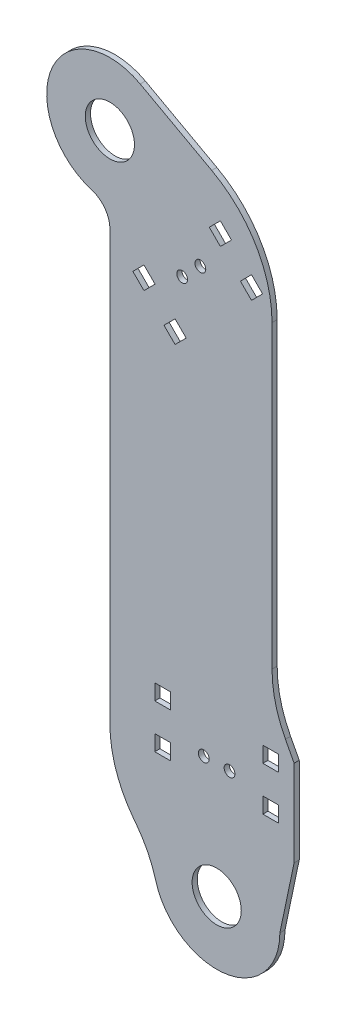
SolidWorks part; units mm, degrees
ref_plane "前视基准面" through (0, 0, 0) normal (0, 0, 1) x (1, 0, 0)
ref_plane "上视基准面" through (0, 0, 0) normal (0, 1, 0) x (1, 0, 0)
ref_plane "右视基准面" through (0, 0, 0) normal (1, 0, 0) x (0, 0, -1)
sketch "草图1" plane through (0, 0, 0) normal (0, 0, 1) x (1, 0, 0)
  line L0 (-10.1959, 211.8389) -> (-55.1959, 211.8389) construction
  line L1 (-10.1959, 211.8389) -> (21.6239, 180.0191) construction
  line L4 (17.8913, 176.6806) -> (24.9624, 183.7517) construction
  line L6 (26.7655, 181.9485) -> (19.6944, 174.8775) construction
  line L8 (23.9371, 177.7059) -> (9.0878, 162.8567) construction
  line L10 (21.6239, 180.0191) -> (23.9371, 177.7059) construction
  line L12 (23.9371, 177.7059) -> (29.9828, 171.6601) construction
  line L18 (29.9828, 171.6601) -> (15.1336, 156.8109) construction
  line L20 (15.1336, 156.8109) -> (9.0878, 162.8567) construction
  line L21 (15.1336, 152.4975) -> (19.447, 156.8109)
  line L22 (15.1336, 152.4975) -> (10.8203, 156.8109)
  line L23 (19.447, 156.8109) -> (15.1336, 161.1242)
  line L24 (10.8203, 156.8109) -> (15.1336, 161.1242)
  line L25 (15.1336, 152.4975) -> (15.1336, 161.1242) construction
  line L26 (19.447, 156.8109) -> (10.8203, 156.8109) construction
  line L27 (3.0421, 164.5891) -> (7.3554, 168.9024)
  line L28 (3.0421, 173.2158) -> (7.3554, 168.9024)
  line L29 (-1.2713, 168.9024) -> (3.0421, 173.2158)
  line L30 (-1.2713, 168.9024) -> (3.0421, 164.5891)
  line L31 (44.8321, 182.196) -> (40.5187, 186.5094)
  line L32 (49.1454, 186.5094) -> (44.8321, 190.8227)
  line L33 (49.1454, 186.5094) -> (44.8321, 182.196)
  line L34 (44.8321, 190.8227) -> (40.5187, 186.5094)
  line L35 (37.0539, 198.6009) -> (32.7406, 194.2875)
  line L36 (32.7406, 202.9143) -> (28.4272, 198.6009)
  line L37 (28.4272, 198.6009) -> (32.7406, 194.2875)
  line L38 (32.7406, 202.9143) -> (37.0539, 198.6009)
  line L39 (18.0883, 240.1232) -> (52.8041, 205.4074) construction
  line L49 (52.8041, 93.3389) -> (-10.1959, 93.3389) construction
  line L50 (-29.6695, 176.8992) -> (-10.1959, 166.0457) construction
  line L53 (-10.1959, 93.3389) -> (-10.1959, 166.0457)
  line L54 (52.8041, 93.3389) -> (52.8041, 205.4074)
  line L58 (21.3041, 93.3389) -> (21.3041, -25.1611) construction
  line L96 (7.2541, 34.7103) -> (13.3541, 34.7103)
  line L97 (7.2541, 34.7103) -> (7.2541, 28.6103)
  line L98 (7.2541, 28.6103) -> (13.3541, 28.6103)
  line L99 (13.3541, 34.7103) -> (13.3541, 28.6103)
  line L100 (7.2541, 34.7103) -> (13.3541, 28.6103) construction
  line L101 (7.2541, 28.6103) -> (13.3541, 34.7103) construction
  line L102 (7.2541, 17.6103) -> (13.3541, 17.6103)
  line L103 (7.2541, 11.5103) -> (7.2541, 17.6103)
  line L104 (7.2541, 11.5103) -> (13.3541, 11.5103)
  line L105 (13.3541, 11.5103) -> (13.3541, 17.6103)
  line L116 (52.8041, 93.3389) -> (52.8041, 8.5694) construction
  line L117 (31.3041, -25.1611) -> (31.3041, 2.2062) construction
  line L118 (49.2541, 11.5103) -> (49.2541, 17.6103)
  line L119 (55.3541, 11.5103) -> (49.2541, 11.5103)
  line L120 (55.3541, 11.5103) -> (55.3541, 17.6103)
  line L121 (55.3541, 17.6103) -> (49.2541, 17.6103)
  line L122 (55.3541, 28.6103) -> (49.2541, 34.7103) construction
  line L123 (55.3541, 34.7103) -> (49.2541, 28.6103) construction
  line L124 (49.2541, 34.7103) -> (49.2541, 28.6103)
  line L125 (55.3541, 28.6103) -> (49.2541, 28.6103)
  line L126 (55.3541, 34.7103) -> (55.3541, 28.6103)
  line L127 (55.3541, 34.7103) -> (49.2541, 34.7103)
  line L128 (52.8041, 93.3389) -> (52.8041, 50.9542)
  line L129 (52.8041, 50.9542) -> (61.3871, 34.7103)
  line L130 (61.3871, 34.7103) -> (61.3871, 1.202)
  line L131 (-10.1959, 93.3389) -> (-10.1959, -3.1129)
  line L132 (-10.1959, -3.1129) -> (-8.6959, -25.1611) construction
  line L133 (-10.1959, 166.0457) -> (-10.1959, 187.2889)
  line L134 (52.8041, 205.4074) -> (1.5704, 233.3855)
  line L135 (-10.1959, -3.1129) -> (6.7541, -25.1611)
  line L136 (61.3871, 1.202) -> (55.8541, -25.1611)
  circle A0 centre (-10.1959, 211.8389) radius 9.55
  circle A1 centre (-10.1959, 211.8389) radius 40 construction
  circle A6 centre (-10.1959, 211.8389) radius 20.528 construction
  circle A8 centre (-10.1959, 211.8389) radius 45 construction
  circle A9 centre (24.9624, 183.7517) radius 2.55 construction
  circle A10 centre (17.8913, 176.6806) radius 2.55 construction
  arc A13 (18.0883, 240.1232) -> (-29.6695, 176.8992) centre (-10.1959, 211.8389) ccw construction
  circle A21 centre (21.3041, -25.1611) radius 40 construction
  circle A25 centre (26.3041, 19.5603) radius 2.55 construction
  circle A26 centre (21.3041, -25.1611) radius 5.05 construction
  circle A27 centre (31.3041, -25.1611) radius 9.55
  circle A28 centre (31.3041, -25.1611) radius 40 construction
  circle A30 centre (36.3041, 19.5603) radius 2.55 construction
  arc A31 (-8.6959, -25.1611) -> (61.3871, 1.202) centre (31.3041, -25.1611) ccw construction
  circle A32 centre (26.3041, 19.5603) radius 2.1
  circle A33 centre (36.3041, 19.5603) radius 2.1
  circle A34 centre (17.8913, 176.6806) radius 2.1
  circle A35 centre (24.9624, 183.7517) radius 2.1
  circle A36 centre (-10.1959, 211.8389) radius 24.55 construction
  arc A37 (-10.1959, 187.2889) -> (1.5704, 233.3855) centre (-10.1959, 211.8389) cw
  circle A38 centre (31.3041, -25.1611) radius 24.55 construction
  arc A39 (6.7541, -25.1611) -> (55.8541, -25.1611) centre (31.3041, -25.1611) ccw
  dimension "D10" = 19.1
  dimension "D13" = 80
  dimension "D14" = 118.5
  dimension "D5" = 1
  dimension "D6" = 90
  dimension "D3" = 5.1
  dimension "D12" = 80
  dimension "D16" = 15
  dimension "D17" = 5.1
  dimension "D18" = 15
  dimension "D25" = 10
  dimension "D26" = 19.1
  dimension "D2" = 135
  dimension "D4" = 10
  dimension "D7" = 21
  dimension "D8" = 8.55
  dimension "D9" = 6.1
  dimension "D11" = 6.1
  dimension "D15" = 118.5
  dimension "D23" = 6.1
  dimension "D24" = 6.1
extrude "凸台-拉伸2" add sketch "草图1" along normal blind 2
fillet "圆角1" radius 45 4 edges at (6.7541, -25.1611, 1) (-10.1959, -3.1129, 1) (52.8041, 50.9542, 1) (52.8041, 205.4074, 1)
fillet "圆角2" radius 10 1 edges at (-10.1959, 187.2889, 1)
